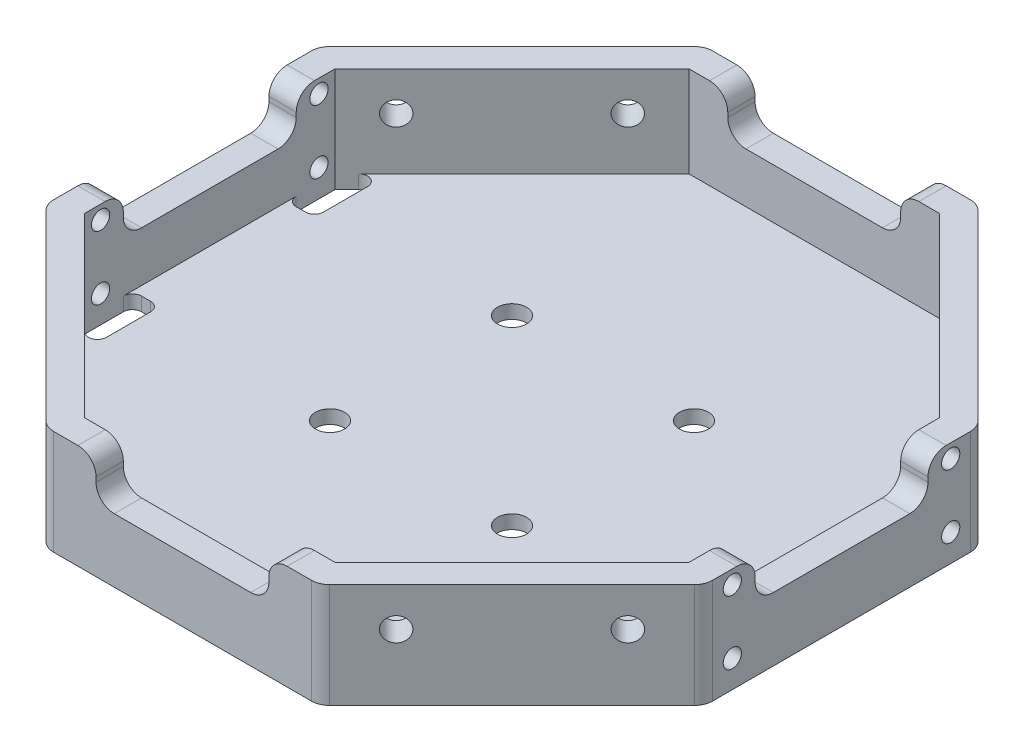
SolidWorks part; units mm, degrees
ref_plane "Front Plane" through (0, 0, 0) normal (0, 0, 1) x (1, 0, 0)
ref_plane "Top Plane" through (0, 0, 0) normal (0, 1, 0) x (1, 0, 0)
ref_plane "Right Plane" through (0, 0, 0) normal (1, 0, 0) x (0, 0, -1)
sketch "Sketch1" plane through (0, 0, 0) normal (0, 1, 0) x (1, 0, 0)
  line L1 (-11.2132, 40) -> (18.7868, 40)
  line L2 (18.7868, 40) -> (40, 18.7868)
  line L3 (40, 18.7868) -> (40, -11.2132)
  line L5 (-32.4264, 18.7868) -> (-32.4264, -11.2132)
  line L6 (-11.2132, 40) -> (-32.4264, 18.7868)
  line L7 (18.7868, -32.4264) -> (40, -11.2132)
  line L8 (-11.2132, -32.4264) -> (18.7868, -32.4264)
  line L9 (-11.2132, -32.4264) -> (-32.4264, -11.2132)
  point P13 (-32.4264, 3.7868)
  dimension "D1" = 30
  dimension "D2" = 30
  dimension "D3" = 40
  dimension "D4" = 40
extrude "Boss-Extrude1" add sketch "Sketch1" along normal blind 11.5
shell "Shell1" thickness 3
sketch "Sketch3" plane through (-21.8198, 0, 21.8198) normal (-0.7071, 0, 0.7071) x (0.7071, 0, 0.7071)
  line L0 (0, 11.5) -> (0, 7.25) construction
  line L1 (-15, 11.5) -> (15, 11.5) construction
  line L2 (0, 7.25) -> (9, 7.25) construction
  line L3 (0, 7.25) -> (-9, 7.25) construction
  circle A0 centre (-9, 7.25) radius 1.3
  circle A1 centre (9, 7.25) radius 1.3
extrude "Cut-Extrude1" cut sketch "Sketch3" against normal blind 94
sketch "Sketch4" plane through (-25.6066, 0, -25.6066) normal (-0.7071, 0, -0.7071) x (-0.7071, 0, 0.7071)
  line L0 (-5.3553, 11.5) -> (-5.3553, 7.25) construction
  line L1 (-20.3553, 11.5) -> (9.6447, 11.5) construction
  line L2 (-5.3553, 7.25) -> (-14.3553, 7.25) construction
  line L3 (-5.3553, 7.25) -> (3.6447, 7.25) construction
  circle A0 centre (-14.3553, 7.25) radius 1.3
  circle A1 centre (3.6447, 7.25) radius 1.3
extrude "Cut-Extrude2" cut sketch "Sketch4" against normal blind 94
fillet "Fillet1" radius 2 8 edges at (40, 5.75, 11.2132) (18.7868, 5.75, 32.4264) (40, 5.75, -18.7868) (18.7868, 5.75, -40) (-11.2132, 5.75, -40) (-32.4264, 5.75, -18.7868) (-32.4264, 5.75, 11.2132) (-11.2132, 5.75, 32.4264)
sketch "Sketch5" plane through (0, 0, 32.4264) normal (0, 0, 1) x (1, 0, 0)
  line L0 (3.7868, 11.5) -> (3.7868, 7) construction
  line L1 (-10.3848, 11.5) -> (17.9584, 11.5) construction
  line L2 (3.7868, 7) -> (13.2868, 7)
  line L3 (13.2868, 7) -> (13.2868, 11.5)
  line L4 (3.7868, 7) -> (-5.7132, 7)
  line L5 (-5.7132, 7) -> (-5.7132, 11.5)
  line L6 (-5.7132, 11.5) -> (13.2868, 11.5)
  dimension "D1" = 9.5
extrude "Cut-Extrude3" cut sketch "Sketch5" against normal blind 79
sketch "Sketch6" plane through (-32.4264, 0, 0) normal (-1, 0, 0) x (0, 0, 1)
  line L0 (-3.7868, 11.5) -> (-3.7868, 7) construction
  line L1 (-17.9584, 11.5) -> (10.3848, 11.5) construction
  line L2 (-3.7868, 7) -> (5.7132, 7)
  line L3 (5.7132, 7) -> (5.7132, 11.5)
  line L4 (-3.7868, 7) -> (-13.2868, 7)
  line L5 (-13.2868, 7) -> (-13.2868, 11.5)
  line L6 (-13.2868, 11.5) -> (5.7132, 11.5)
  dimension "D1" = 9.5
extrude "Cut-Extrude4" cut sketch "Sketch6" against normal blind 79
fillet "Fillet2" radius 2 16 edges at (38.5, 11.5, 5.7132) (38.5, 7, 5.7132) (38.5, 11.5, -13.2868) (38.5, 7, -13.2868) (13.2868, 11.5, 30.9264) (13.2868, 7, 30.9264) (-5.7132, 11.5, 30.9264) (-5.7132, 7, 30.9264) (-30.9264, 11.5, -13.2868) (-30.9264, 7, -13.2868) (-30.9264, 11.5, 5.7132) (-30.9264, 7, 5.7132) (13.2868, 11.5, -38.5) (13.2868, 7, -38.5) (-5.7132, 11.5, -38.5) (-5.7132, 7, -38.5)
sketch "Sketch7" plane through (0, 0, 0) normal (0, -1, 0) x (-1, 0, 0)
  circle A0 centre (6.2132, -6.2132) radius 1.6
  circle A1 centre (-13.7868, -6.2132) radius 1.6
  circle A2 centre (-13.7868, 13.7868) radius 1.6
  circle A3 centre (6.2132, 13.7868) radius 1.6
extrude "Cut-Extrude5" cut sketch "Sketch7" against normal blind 10
sketch "Sketch8" plane through (40, 0, 0) normal (1, 0, 0) x (0, 0, -1)
  line L0 (3.7868, 7) -> (-8.2132, 7) construction
  line L1 (11.2868, 7) -> (-3.7132, 7) construction
  line L2 (-8.2132, 7) -> (-8.2132, 10) construction
  line L3 (-8.2132, 7) -> (-8.2132, 3) construction
  line L4 (3.7868, 7) -> (3.7868, 3) construction
  line L5 (15.7868, 7) -> (15.7868, 3) construction
  circle A0 centre (-8.2132, 10) radius 1
  circle A1 centre (-8.2132, 3) radius 1
  circle A2 centre (15.7868, 3) radius 1
  circle A3 centre (15.7868, 10) radius 1
extrude "Cut-Extrude7" cut sketch "Sketch8" against normal blind 79
sketch "Sketch10" plane through (0, 3, 0) normal (0, 1, 0) x (1, 0, 0)
  line L0 (17.5442, 37) -> (37, 17.5442)
  line L1 (37, 17.5442) -> (37, -9.9706)
  line L2 (37, -9.9706) -> (17.5442, -29.4264)
  line L3 (17.5442, -29.4264) -> (-9.9706, -29.4264)
  line L4 (-9.9706, -29.4264) -> (-29.4264, -9.9706)
  line L5 (-29.4264, -9.9706) -> (-29.4264, 17.5442)
  line L6 (-29.4264, 17.5442) -> (-9.9706, 37)
  line L7 (-9.9706, 37) -> (17.5442, 37)
extrude "Cut-Extrude8" cut sketch "Sketch10" against normal blind 1.5
sketch "Sketch12" plane through (0, 1.5, 0) normal (0, 1, 0) x (1, 0, 0)
  line L0 (-29.4264, 17.5442) -> (-26.4264, 20.5442)
  line L1 (-29.4264, -3.7132) -> (-29.4264, 11.2868) construction
  line L2 (-29.4264, -5.7132) -> (-29.4264, -3.7132) construction
  line L3 (-29.4264, -4.7132) -> (-26.4264, -4.7132)
  line L4 (-26.4264, -4.7132) -> (-26.4264, -12.9706)
  line L5 (-29.4264, -9.9706) -> (-9.9706, -29.4264) construction
  line L6 (-29.4264, -4.7132) -> (-29.4264, -9.9706)
  line L7 (-29.4264, -9.9706) -> (-26.4264, -12.9706)
  line L8 (3.7868, 37) -> (3.7868, -29.4264)
  line L9 (-3.7132, 37) -> (11.2868, 37) construction
  line L10 (11.2868, -29.4264) -> (-3.7132, -29.4264) construction
  line L11 (-29.4264, 3.7868) -> (37, 3.7868)
  line L12 (37, 11.2868) -> (37, -3.7132) construction
  line L13 (-29.4264, 12.2868) -> (-29.4264, 17.5442)
  line L14 (-26.4264, 12.2868) -> (-26.4264, 20.5442)
  line L15 (-29.4264, 12.2868) -> (-26.4264, 12.2868)
  line L16 (37, -9.9706) -> (34, -12.9706)
  line L17 (37, -4.7132) -> (37, -9.9706)
  line L18 (34, -4.7132) -> (34, -12.9706)
  line L19 (37, -4.7132) -> (34, -4.7132)
  line L20 (37, 12.2868) -> (34, 12.2868)
  line L21 (34, 12.2868) -> (34, 20.5442)
  line L22 (37, 12.2868) -> (37, 17.5442)
  line L23 (37, 17.5442) -> (34, 20.5442)
  line M6 (-9.9706, 37) -> (-29.4264, 17.5442)
  line M7 (-29.4264, 17.5442) -> (-29.4264, -9.9706)
  line M8 (-29.4264, -9.9706) -> (-9.9706, -29.4264)
  line M10 (17.5442, -29.4264) -> (37, -9.9706)
  line M11 (37, -9.9706) -> (37, 17.5442)
  line M12 (37, 17.5442) -> (17.5442, 37)
extrude "Cut-Extrude9" cut sketch "Sketch12" against normal blind 1.5 contours L15 L14 M7 M6 | L4 L3 M7 M8 | L21 L20 M11 M12 | L19 L18 M11 M10
fillet "Fillet3" radius 1 12 edges at (34, 0.75, -12.2868) (34, 0.75, -20.5442) (37, 0.75, -12.2868) (34, 0.75, 4.7132) (37, 0.75, 4.7132) (34, 0.75, 12.9706) (-26.4264, 0.75, 4.7132) (-26.4264, 0.75, 12.9706) (-29.4264, 0.75, 4.7132) (-26.4264, 0.75, -12.2868) (-29.4264, 0.75, -12.2868) (-26.4264, 0.75, -20.5442)
